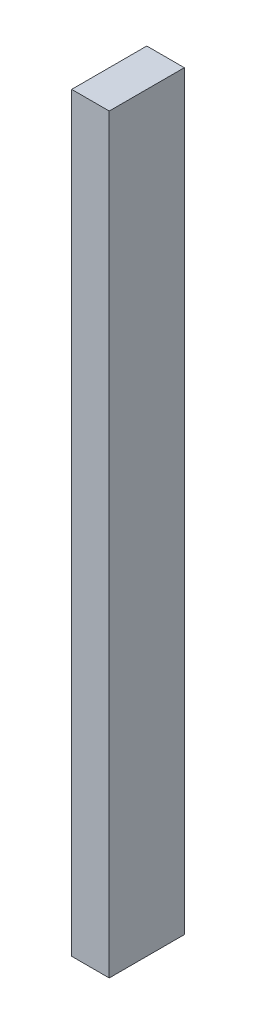
SolidWorks part; units mm, degrees
ref_plane "Спереди" through (0, 0, 0) normal (0, 0, 1) x (1, 0, 0)
ref_plane "Сверху" through (0, 0, 0) normal (0, 1, 0) x (1, 0, 0)
ref_plane "Справа" through (0, 0, 0) normal (1, 0, 0) x (0, 0, -1)
other "Configuration Table"
sketch "Эскиз1" plane through (0, 0, 0) normal (0, 1, 0) x (1, 0, 0)
  line L1 (12.5, 25) -> (-12.5, 25)
  line L2 (12.5, 25) -> (12.5, -25)
  line L3 (12.5, -25) -> (-12.5, -25)
  line L4 (-12.5, 25) -> (-12.5, -25)
  line L5 (12.5, 25) -> (-12.5, -25) construction
  line L6 (12.5, -25) -> (-12.5, 25) construction
  point P0 (0, 0)
extrude "Бобышка-Вытянуть1" add sketch "Эскиз1" along normal blind 550
sketch "Эскиз2" plane through (0, 550, 0) normal (0, 1, 0) x (1, 0, 0)
  circle A0 centre (0, 0) radius 4
extrude "Вырез-Вытянуть1" cut sketch "Эскиз2" against normal blind 10
sketch "Эскиз3" plane through (0, 0, 0) normal (0, -1, 0) x (1, 0, 0)
  circle A0 centre (0, 0) radius 4
extrude "Вырез-Вытянуть2" cut sketch "Эскиз3" against normal blind 10
sketch "Эскиз4" plane through (0, 550, 0) normal (0, 1, 0) x (1, 0, 0)
  line L4 (-12.5, 25) -> (-12.5, -25)
  line L5 (-12.5, -25) -> (12.5, -25)
  line L6 (12.5, -25) -> (12.5, 25)
  line L7 (12.5, 25) -> (-12.5, 25)
  line L8 (-12.5, 25) -> (-12.5, -25)
  line L9 (-12.5, -25) -> (12.5, -25)
  line L10 (12.5, -25) -> (12.5, 25)
  line L11 (12.5, 25) -> (-12.5, 25)
  dimension "D1" = 0
extrude "Вырез-Вытянуть3" cut sketch "Эскиз4" against normal blind 50
